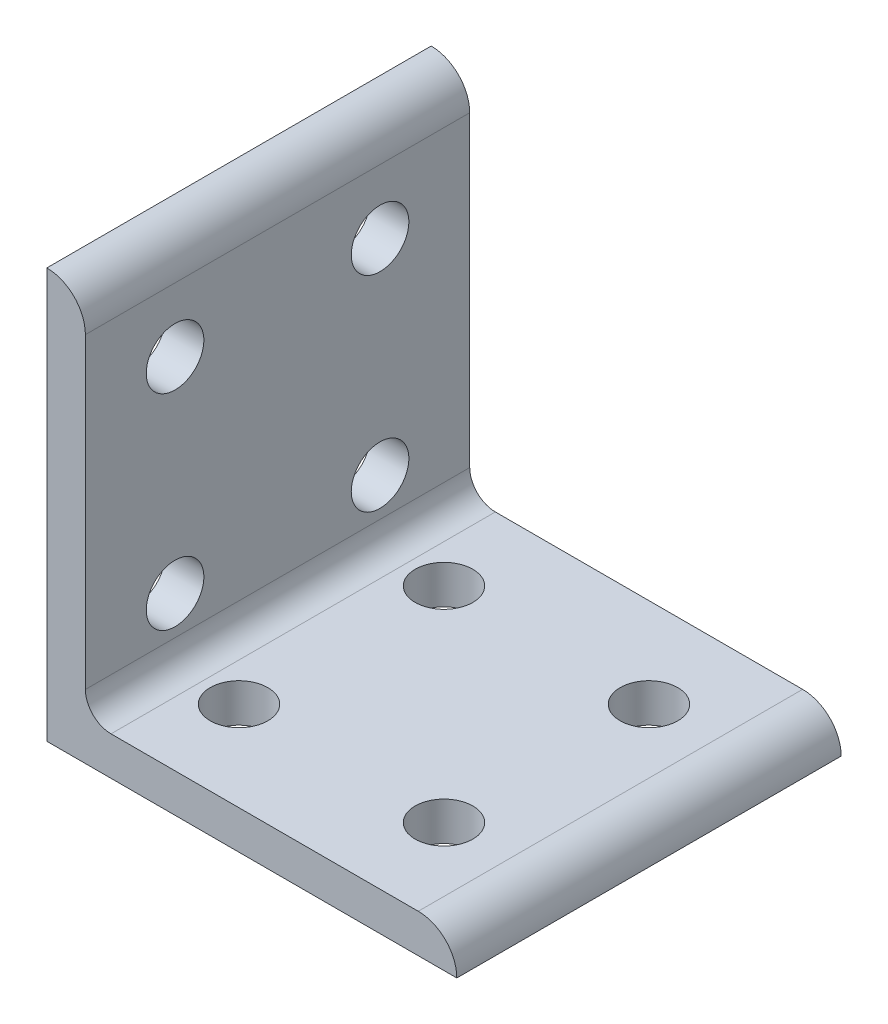
SolidWorks part; units mm, degrees
ref_plane "Front Plane" through (0, 0, 0) normal (0, 0, 1) x (1, 0, 0)
ref_plane "Top Plane" through (0, 0, 0) normal (0, 1, 0) x (1, 0, 0)
ref_plane "Right Plane" through (0, 0, 0) normal (1, 0, 0) x (0, 0, -1)
sketch "Sketch1" plane through (0, 0, 0) normal (0, 0, 1) x (1, 0, 0)
  line L0 (0, 0) -> (0, 50.8)
  line L1 (4.7752, 46.0248) -> (4.7752, 50.8) construction
  line L2 (4.7752, 46.0248) -> (4.7752, 7.9502)
  line L3 (7.9502, 4.7752) -> (46.0248, 4.7752)
  line L4 (4.7752, 50.8) -> (0, 50.8) construction
  line L5 (50.8, 0) -> (0, 0)
  line L6 (46.0248, 4.7752) -> (50.8, 4.7752) construction
  line L7 (50.8, 4.7752) -> (50.8, 0) construction
  arc A0 (4.7752, 46.0248) -> (0, 50.8) centre (0, 46.0248) ccw
  arc A1 (50.8, 0) -> (46.0248, 4.7752) centre (46.0248, 0) ccw
  arc A2 (4.7752, 7.9502) -> (7.9502, 4.7752) centre (7.9502, 7.9502) ccw
  point P10 (4.7752, 48.4124)
  dimension "E" = 3.175
  dimension "D" = 4.7752
  dimension "C" = 50.8
  dimension "B" = 50.8
extrude "Boss-Extrude1" add sketch "Sketch1" along normal mid plane 47.625
sketch "Sketch2" plane through (0, 0, 0) normal (0, 1, 0) x (1, 0, 0)
  line L0 (0, -12.7) -> (12.7, -12.7) construction
  line L1 (12.7, -12.7) -> (38.1, -12.7) construction
  line L2 (0, -12.7) -> (0, 12.7) construction
  line L3 (0, 12.7) -> (12.7, 12.7) construction
  line L4 (38.1, 12.7) -> (38.1, -12.7) construction
  line L5 (0, -12.7) -> (0, -23.8125) construction
  line L6 (12.7, -12.7) -> (12.7, 12.7) construction
  line L7 (12.7, 12.7) -> (38.1, 12.7) construction
  circle A0 centre (12.7, -12.7) radius 3.5687
  circle A1 centre (38.1, -12.7) radius 3.5687
  circle A2 centre (12.7, 12.7) radius 3.5687
  circle A3 centre (38.1, 12.7) radius 3.5687
  dimension "D1" = 12.7
  dimension "E" = 7.1374
  dimension "D2" = 25.4
  dimension "D3" = 11.1125
  dimension "D4" = 25.4
extrude "Cut-Extrude1" cut sketch "Sketch2" along normal through all
sketch "Sketch3" plane through (0, 0, 0) normal (1, 0, 0) x (0, 0, -1)
  line L0 (-12.7, 0) -> (-12.7, 12.7) construction
  line L1 (-12.7, 12.7) -> (-12.7, 38.1) construction
  line L2 (12.7, 0) -> (12.7, 12.7) construction
  line L3 (12.7, 12.7) -> (-12.7, 12.7) construction
  line L4 (12.7, 12.7) -> (12.7, 38.1) construction
  line L5 (12.7, 38.1) -> (-12.7, 38.1) construction
  circle A0 centre (-12.7, 12.7) radius 3.5687
  circle A1 centre (-12.7, 38.1) radius 3.5687
  circle A2 centre (12.7, 12.7) radius 3.5687
  circle A3 centre (12.7, 38.1) radius 3.5687
  dimension "D1" = 12.7
  dimension "D2" = 25.4
  dimension "E" = 7.1374
extrude "Cut-Extrude2" cut sketch "Sketch3" along normal through all
equation "\"E@Sketch3\" = \"E@Sketch2\""
equation "\"D1@Sketch3\" = \"D1@Sketch2\""
equation "\"D2@Sketch3\" = \"D2@Sketch2\""
